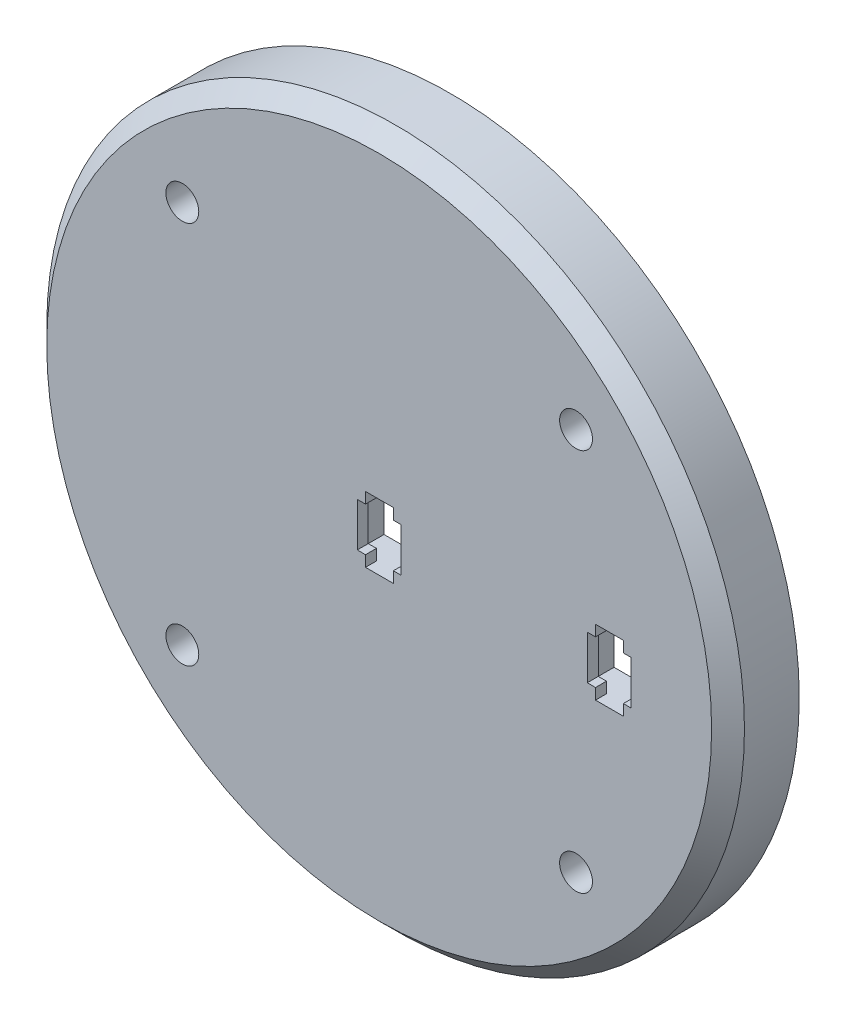
SolidWorks part; units mm, degrees
ref_plane "Front Plane" through (0, 0, 0) normal (0, 0, 1) x (1, 0, 0)
ref_plane "Top Plane" through (0, 0, 0) normal (0, 1, 0) x (1, 0, 0)
ref_plane "Right Plane" through (0, 0, 0) normal (1, 0, 0) x (0, 0, -1)
ref_plane "Plane1" through (0, 0, -25.5) normal (0, 0, 1) x (1, 0, 0)
sketch "Sketch2" plane through (0, 0, -25.5) normal (0, 0, 1) x (1, 0, 0)
  circle A0 centre (0, 0) radius 32 construction
  circle A1 centre (0, 0) radius 31.85
  dimension "D1" = 64
  dimension "D2" = 0.15
extrude "Boss-Extrude1" add sketch "Sketch2" against normal blind 6.5
sketch "Sketch3" plane through (0, 0, -32) normal (0, 0, -1) x (-1, 0, 0)
  line L0 (-18, 3) -> (-24, 3)
  line L1 (3, 3) -> (-3, 3)
  line L2 (3, 3) -> (3, -3)
  line L3 (3, -3) -> (-3, -3)
  line L4 (-3, 3) -> (-3, -3)
  line L5 (3, 3) -> (-3, -3) construction
  line L6 (3, -3) -> (-3, 3) construction
  line L7 (-18, 3) -> (-18, -3)
  line L8 (-18, -3) -> (-24, -3)
  line L9 (-24, 3) -> (-24, -3)
  line L10 (-18, 3) -> (-24, -3) construction
  line L11 (-18, -3) -> (-24, 3) construction
  point P0 (0, 0)
  point P7 (-21, 0)
  dimension "D1" = 6
  dimension "D2" = 6
  dimension "D3" = 2
extrude "Cut-Extrude1" cut sketch "Sketch3" against normal blind 6.5
chamfer "Chamfer1" distance 6 angle 27 8 edges at (3, 0, -32) (0, -3, -32) (-3, 0, -32) (0, 3, -32) (18, 0, -32) (21, 3, -32) (24, 0, -32) (21, -3, -32)
sketch "Sketch5" plane through (0, 0, 0) normal (0, 0, 1) x (1, 0, 0)
  line L0 (0, -31.6068) -> (0, 32) construction
  line L2 (-31.85, 0) -> (31.85, 0) construction
  circle A0 centre (-17.9719, -17.5002) radius 1.5
  arc A1 (28.3907, 14.7638) -> (-28.3907, 14.7638) centre (0, 0) ccw construction
  circle A2 centre (0, 0) radius 31.85 construction
  circle A3 centre (17.9719, -17.5002) radius 1.5
  circle A4 centre (17.9719, 17.5002) radius 1.5
  circle A5 centre (-17.9719, 17.5002) radius 1.5
  point P12 (-17.9719, -17.5002)
extrude "Cut-Extrude2" cut sketch "Sketch5" against normal through all
sketch "Sketch6" plane through (0, 0, -32) normal (0, 0, 1) x (1, 0, 0)
  line L0 (0, -32) -> (0, 32) construction
  line L2 (-32, 0) -> (31.85, 0) construction
  circle A0 centre (-17.9719, -17.5002) radius 2.5
  arc A1 (-28.3907, -14.7638) -> (28.3907, -14.7638) centre (0, 0) ccw construction
  circle A2 centre (0, 0) radius 32 construction
  arc A3 (-28.3907, 14.7638) -> (-28.3907, -14.7638) centre (0, 0) ccw construction
  circle A4 centre (0, 0) radius 31.85 construction
  circle A5 centre (17.9719, -17.5002) radius 2.5
  circle A6 centre (17.9719, 17.5002) radius 2.5
  circle A7 centre (-17.9719, 17.5002) radius 2.5
extrude "Cut-Extrude3" cut sketch "Sketch6" along normal blind 3
chamfer "Chamfer3" distance 1.5 angle 45 1 edges at (31.85, 0, -25.5)
sketch "Sketch7" plane through (0, 0, -25.5) normal (0, 0, 1) x (1, 0, 0)
  line L0 (0, 0) -> (21.0054, 0) construction
  line L1 (10.5027, 0) -> (10.5027, 9.0294) construction
  line L2 (-2, -2) -> (-2, 2)
  line L3 (-3, -3) -> (3, -3) construction
  line L4 (-3, -3) -> (-3, 3)
  line L5 (-3, 3) -> (3, 3) construction
  line L6 (3, -3) -> (3, 3)
  line L7 (-3, -3) -> (3, 3) construction
  line L8 (-3, 3) -> (3, -3) construction
  line L9 (-2, 2) -> (2, 2) construction
  line L10 (2, -2) -> (2, 2)
  line L11 (-2, -2) -> (2, -2) construction
  line L12 (-2, -2) -> (-1.25, -2)
  line L13 (-1.25, -2) -> (-1.25, -3)
  line L14 (0.0205, 0) -> (0.0205, -2.4966) construction
  line L15 (-1.25, 2) -> (-1.25, 3)
  line L16 (-2, 2) -> (-1.25, 2)
  line L17 (1.2909, -2) -> (1.2909, -3)
  line L18 (2.0409, -2) -> (1.2909, -2)
  line L19 (2.0409, 2) -> (1.2909, 2)
  line L20 (1.2909, 2) -> (1.2909, 3)
  line L21 (19, -2) -> (19, 2)
  line L22 (18, -3) -> (18, 3)
  line L23 (-1.25, -3) -> (-3, -3)
  line L24 (-1.25, 3) -> (-3, 3)
  line L25 (1.2909, 3) -> (3, 3)
  line L26 (1.2909, -3) -> (3, -3)
  line L27 (24, -3) -> (24, 3)
  line L28 (23, -2) -> (23, 2)
  line L29 (19, -2) -> (19.75, -2)
  line L30 (19.75, -2) -> (19.75, -3)
  line L31 (19.75, 2) -> (19.75, 3)
  line L32 (19, 2) -> (19.75, 2)
  line L33 (22.2909, -2) -> (22.2909, -3)
  line L34 (23.0409, -2) -> (22.2909, -2)
  line L35 (23.0409, 2) -> (22.2909, 2)
  line L36 (22.2909, 2) -> (22.2909, 3)
  line L37 (19.75, -3) -> (18, -3)
  line L38 (19.75, 3) -> (18, 3)
  line L39 (22.2909, 3) -> (24, 3)
  line L40 (22.2909, -3) -> (24, -3)
  line L41 (18, -3) -> (24, -3) construction
  line L42 (18, 3) -> (24, 3) construction
  line L43 (18, -3) -> (24, 3) construction
  line L44 (18, 3) -> (24, -3) construction
  line L45 (19, 2) -> (23, 2) construction
  line L46 (19, -2) -> (23, -2) construction
  line L47 (21.0205, 0) -> (21.0205, -2.4966) construction
  dimension "D2" = 0.75
  dimension "D1" = 1
  dimension "D3" = 2
extrude "Boss-Extrude2" add sketch "Sketch7" against normal blind 1
sketch "Sketch8" plane through (0, 0, 0) normal (0, 0, 1) x (1, 0, 0)
  line L1 (-10, 10) -> (10, 10)
  line L2 (-10, 10) -> (-10, -10)
  line L3 (-10, -10) -> (10, -10)
  line L4 (10, 10) -> (10, -10)
  line L5 (-10, 10) -> (10, -10) construction
  line L6 (-10, -10) -> (10, 10) construction
  circle A0 centre (0, 0) radius 38.5221
  point P0 (0, 0)
  dimension "D1" = 20
  dimension "D2" = 20
extrude "Cut-Extrude4" [suppressed] cut sketch "Sketch8" against normal through all
